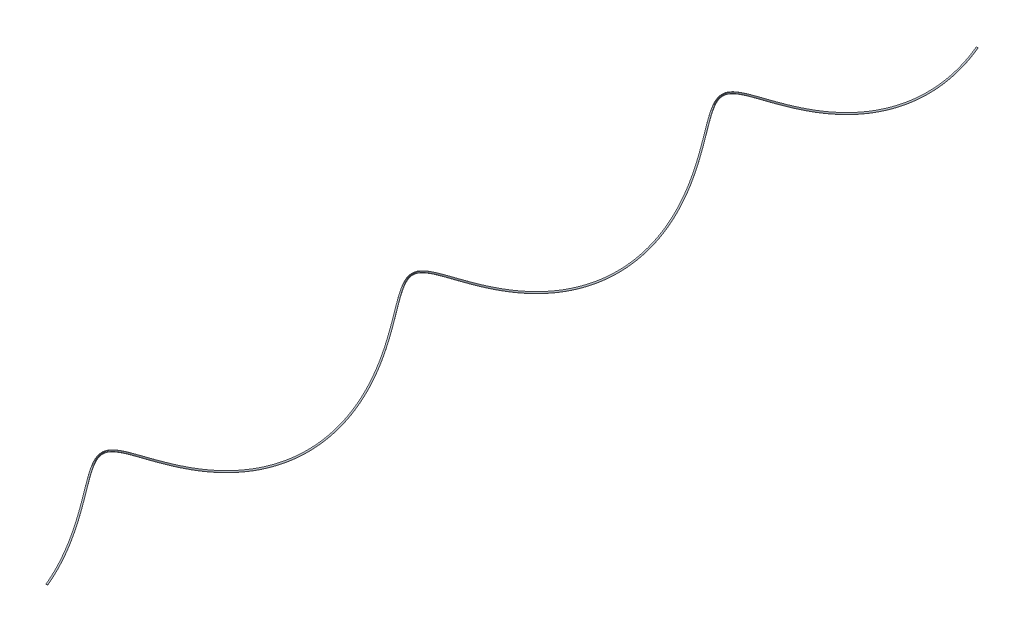
SolidWorks part; units mm, degrees
ref_plane "Front Plane" through (0, 0, 0) normal (0, 0, 1) x (1, 0, 0)
ref_plane "Top Plane" through (0, 0, 0) normal (0, 1, 0) x (1, 0, 0)
ref_plane "Right Plane" through (0, 0, 0) normal (1, 0, 0) x (0, 0, -1)
sketch "Sketch3" plane through (0, 0, 0) normal (0, 0, 1) x (1, 0, 0)
  circle A0 centre (0, 0) radius 2.5
  dimension "D1" = 5
curve "Helix/Spiral1" pitch 21.3333 height 64 turns 3
ref_plane "Plane1" through (2.5, 0, 0) normal (0, -0.5929, 0.8053) x (-1, 0, 0)
sketch "Sketch4" plane through (2.5, 0, 0) normal (0, -0.5929, 0.8053) x (-1, 0, 0)
  circle A0 centre (0.047, 0) radius 0.05
  dimension "D1" = 0.1
sweep "Sweep1" add profiles "Sketch4" path "Helix/Spiral1"
